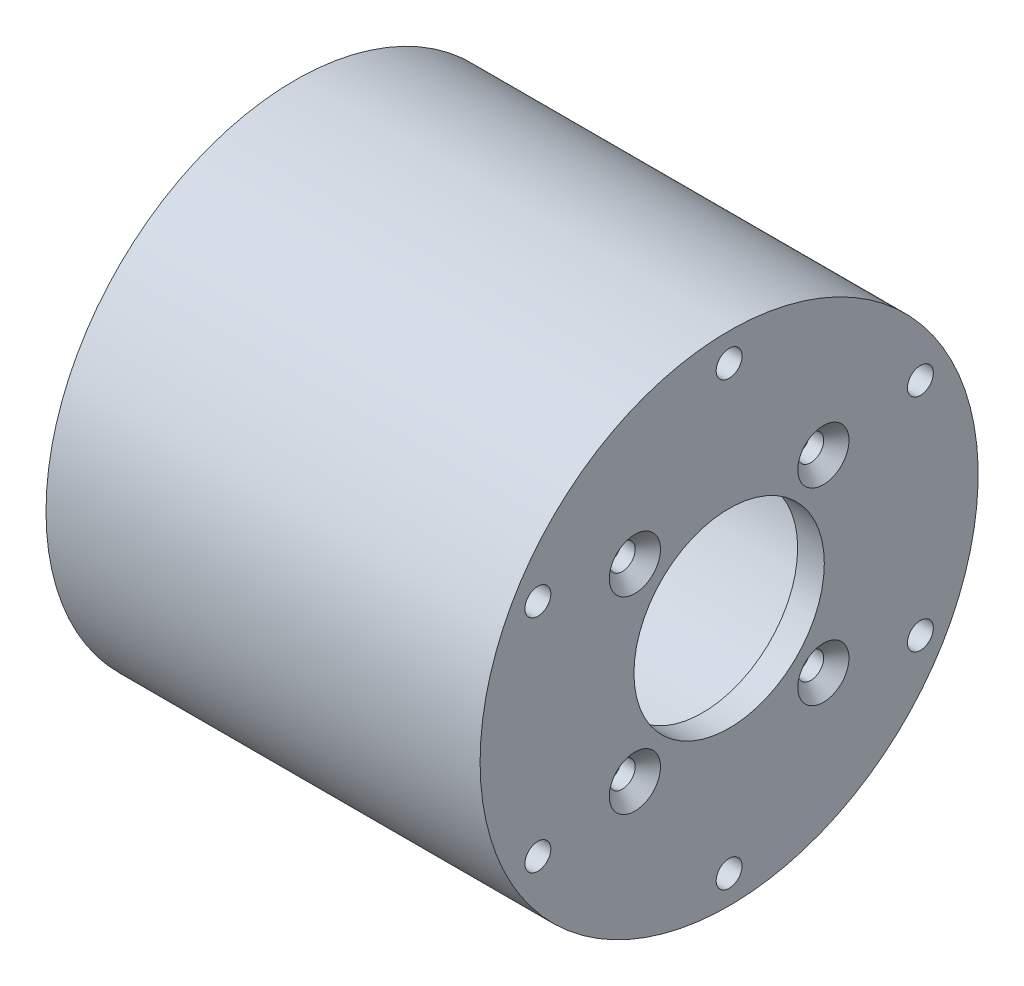
SolidWorks part; units mm, degrees
material "6063-T5"
ref_plane "Front" through (0, 0, 0) normal (0, 0, 1) x (1, 0, 0)
ref_plane "Top" through (0, 0, 0) normal (0, 1, 0) x (1, 0, 0)
ref_plane "Right" through (0, 0, 0) normal (1, 0, 0) x (0, 0, -1)
sketch "Croquis1" plane through (0, 0, 0) normal (1, 0, 0) x (0, 0, -1)
  circle A0 centre (0, 0) radius 21
  circle A1 centre (0, 0) radius 32.7
  dimension "D1" = 42
  dimension "D2" = 65.4
extrude "Saliente-Extruir1" add sketch "Croquis1" along normal mid plane 48.5
sketch "Croquis2" plane through (24.25, 0, 0) normal (1, 0, 0) x (0, 0, -1)
  circle A0 centre (0, 0) radius 12.5
  circle A1 centre (0, 0) radius 32.7 construction
  circle A2 centre (0, 0) radius 32.7
  dimension "D1" = 25
extrude "Saliente-Extruir2" add sketch "Croquis2" along normal blind 3.5
sketch "Croquis3" plane through (-24.25, 0, 0) normal (-1, 0, 0) x (0, 0, 1)
  line L5 (28.6, 0) -> (-28.6, 0) construction
  line L6 (-18, 21) -> (18, 21)
  line L15 (-21, 18) -> (-21, -18)
  line L16 (-18, -21) -> (18, -21)
  line L17 (21, 18) -> (21, -18)
  line L18 (0, -28.6) -> (0, 28.6) construction
  circle A0 centre (0, 0) radius 32.7 construction
  circle A1 centre (0, 0) radius 32.7
  arc A2 (-21, -18) -> (-18, -21) centre (-18, -18) ccw
  arc A3 (18, -21) -> (21, -18) centre (18, -18) ccw
  arc A4 (18, 21) -> (21, 18) centre (18, 18) cw
  arc A5 (-18, 21) -> (-21, 18) centre (-18, 18) ccw
  point P7 (21, 0)
  point P10 (0, 21)
  point P17 (21, -21)
  point P20 (21, 21)
  dimension "D2" = 3
  dimension "D1" = 42
extrude "Saliente-Extruir3" add sketch "Croquis3" along normal blind 5
sketch "Croquis4" plane through (-24.25, 0, 0) normal (-1, 0, 0) x (0, 0, 1)
  line L1 (-15.5, -15.5) -> (15.5, -15.5) construction
  line L2 (-15.5, -15.5) -> (-15.5, 15.5) construction
  line L3 (-15.5, 15.5) -> (15.5, 15.5) construction
  line L4 (15.5, -15.5) -> (15.5, 15.5) construction
  line L5 (-15.5, -15.5) -> (15.5, 15.5) construction
  line L6 (-15.5, 15.5) -> (15.5, -15.5) construction
  circle A0 centre (15.5, 15.5) radius 3.5
  circle A1 centre (-15.5, 15.5) radius 3.5
  circle A2 centre (-15.5, -15.5) radius 3.5
  circle A3 centre (15.5, -15.5) radius 3.5
  point P0 (0, 0)
  dimension "D2" = 7
  dimension "D1" = 31
extrude "Cortar-Extruir1" cut sketch "Croquis4" against normal blind 6
hole_wizard "Refrentado para tornillo tapón con cabeza plana de clavija de M32" positions "Croquis6" profile "Croquis8" countersink size "M3" standard "Ansi Metric"
sketch "Croquis6" plane through (27.75, 0, 0) normal (1, 0, 0) x (0, 0, -1)
  line L1 (-12.375, -12.375) -> (12.375, -12.375) construction
  line L2 (-12.375, -12.375) -> (-12.375, 12.375) construction
  line L3 (-12.375, 12.375) -> (12.375, 12.375) construction
  line L4 (12.375, -12.375) -> (12.375, 12.375) construction
  line L5 (-12.375, -12.375) -> (12.375, 12.375) construction
  line L6 (-12.375, 12.375) -> (12.375, -12.375) construction
  point P1 (12.375, 12.375)
  point P26 (-12.375, -12.375)
  point P27 (-12.375, 12.375)
  point P28 (12.375, -12.375)
  dimension "D1" = 24.75
sketch "Croquis8" plane through (27.75, 12.375, -12.375) normal (0, 1, 0) x (0, 0, -1)
  line L0 (0, 0) -> (0, 4.5205)
  line L1 (0, 4.5205) -> (1.7, 3.499)
  line L2 (1.7, 3.499) -> (1.7, 1.66)
  line L3 (1.7, 1.66) -> (3.36, 0)
  line L5 (3.36, 0) -> (0, 0)
  line L6 (-1.7, 1.66) -> (-3.36, 0) construction
  line L10 (0, 4.5205) -> (-1.7, 3.499) construction
  line L11 (0, -6.35) -> (0, 107.95) construction
  dimension "Diámetro de taladro" = 3.4
  dimension "Profundidad de taladro" = 3.499
  dimension "Ángulo de avellanado cercano" = 6.72
  dimension "Ángulo de avellanado lejano" = 90
  dimension "Ángulo de perforador" = 118
hole_wizard "Taladro de margen para M31" positions "Croquis11" profile "Croquis13" hole size "M3" standard "Ansi Metric"
sketch "Croquis11" plane through (27.75, 0, 0) normal (1, 0, 0) x (0, 0, -1)
  line L0 (0, 28.6) -> (0, -28.6) construction
  line L1 (28.6, 0) -> (-28.6, 0) construction
  point P0 (0, 29)
  point P12 (25.1147, 14.5)
  point P13 (25.1147, -14.5)
  point P14 (0, -29)
  point P15 (-25.1147, -14.5)
  point P16 (-25.1147, 14.5)
  dimension "D1" = 29
  dimension "D2" = 6
sketch "Croquis13" plane through (27.75, 29, 0) normal (0, 1, 0) x (0, 0, -1)
  line L0 (0, 0) -> (0, 16.0215)
  line L1 (0, 16.0215) -> (1.7, 15)
  line L2 (1.7, 15) -> (1.7, 0)
  line L5 (1.7, 0) -> (0, 0)
  line L10 (0, 16.0215) -> (-1.7, 15) construction
  line L11 (0, -6.35) -> (0, 107.95) construction
  dimension "Diámetro de taladro" = 3.4
  dimension "Profundidad de taladro" = 15
  dimension "Ángulo de perforador" = 118
